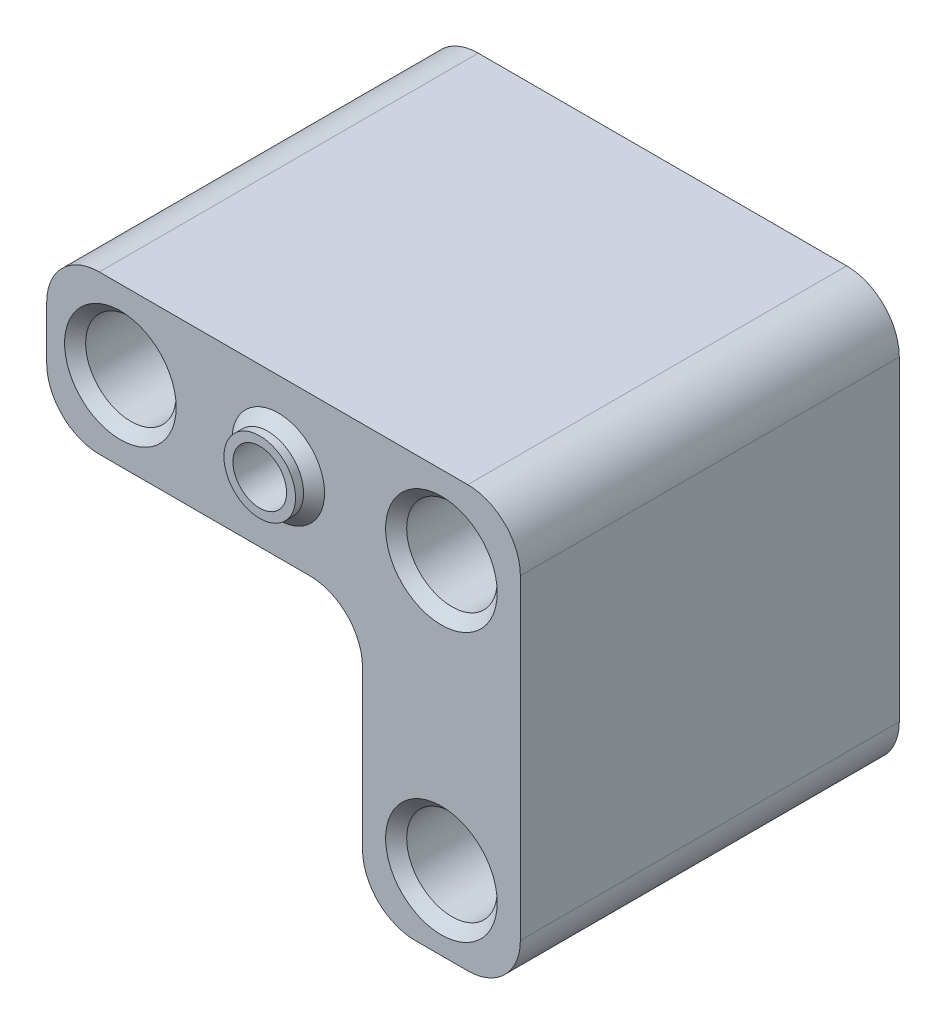
SolidWorks part; units mm, degrees
ref_plane "Front Plane" through (0, 0, 0) normal (0, 0, 1) x (1, 0, 0)
ref_plane "Top Plane" through (0, 0, 0) normal (0, 1, 0) x (1, 0, 0)
ref_plane "Right Plane" through (0, 0, 0) normal (1, 0, 0) x (0, 0, -1)
sketch "Sketch2" plane through (0, 0, 0) normal (0, 0, 1) x (1, 0, 0)
  line L1 (-311.5, 320) -> (-326.5, 320)
  line L2 (-311.5, 320) -> (-311.5, 360)
  line L3 (-311.5, 360) -> (-326.5, 360)
  line L4 (-326.5, 320) -> (-326.5, 360)
  line L5 (-311.5, 360) -> (-281.5, 360)
  line L6 (-311.5, 360) -> (-311.5, 345)
  line L7 (-311.5, 345) -> (-281.5, 345)
  line L8 (-281.5, 360) -> (-281.5, 345)
  line L10 (-281.5, 352.5) -> (-340.0828, 352.5) construction
  line L11 (-319, 320) -> (-319, 373.0529) construction
  line L12 (-303.5, 320) -> (-303.5, 373.0529) construction
  circle A0 centre (-319, 327) radius 2.55
  circle A1 centre (-288.5, 352.5) radius 2.55
  circle A2 centre (-319, 352.5) radius 2.55
  dimension "D7" = 5.1
  dimension "D8" = 5.1
  dimension "D11" = 0
  dimension "D13" = 5.1
  dimension "D1" = 15
  dimension "D2" = 15
  dimension "D4" = 30
  dimension "D5" = 40
  dimension "D9" = 7
  dimension "D10" = 7
  dimension "D12" = 0
extrude "Boss-Extrude1" add sketch "Sketch2" along normal blind 36 contours A1 | A2 | A0 | L2 L1 L4 L3 | L6 L7 L8 L5
sketch "Sketch3" plane through (0, 0, 36) normal (0, 0, 1) x (1, 0, 0)
  circle A0 centre (-319, 352.5) radius 4.3
  circle A1 centre (-319, 327) radius 4.3
  circle A2 centre (-288.5, 352.5) radius 4.3
  dimension "D1" = 8.6
extrude "Cut-Extrude1" cut sketch "Sketch3" against normal blind 30.6
sketch "Sketch4" plane through (0, 0, 0) normal (0, 0, -1) x (-1, 0, 0)
  line L0 (281.5, 352.5) -> (328.8705, 352.5)
  line L1 (281.5, 360) -> (281.5, 345) construction
  line L2 (311.5, 320) -> (311.5, 345) construction
  line L3 (307.55, 354.8383) -> (303.5, 357.1765)
  line L4 (303.5, 357.1765) -> (299.45, 354.8383)
  line L5 (299.45, 354.8383) -> (299.45, 350.1617)
  line L6 (299.45, 350.1617) -> (303.5, 347.8235)
  line L7 (303.5, 347.8235) -> (307.55, 350.1617)
  line L8 (307.55, 350.1617) -> (307.55, 354.8383)
  circle A0 centre (303.5, 352.5) radius 4.05
  circle A1 centre (288.5, 352.5) radius 2.55 construction
  circle A2 centre (303.5, 352.5) radius 4.05 construction
  dimension "D1" = 8.1
  dimension "D3" = 0
  dimension "D2" = 15
extrude "Cut-Extrude2" cut sketch "Sketch4" against normal blind 31.6 contours A0 | L5 L6 L7 L8 L3 L4
fillet "Fillet1" radius 5 6 edges at (-281.5, 360, 18) (-281.5, 345, 18) (-311.5, 345, 18) (-311.5, 320, 18) (-326.5, 320, 18) (-326.5, 360, 18)
chamfer "Chamfer1" distance 1 angle 45 3 edges at (-284.2, 352.5, 36) (-314.7, 352.5, 36) (-314.7, 327, 36)
sketch "Sketch8" plane through (0, 0, 31.6) normal (0, 0, -1) x (-1, 0, 0)
  line L0 (307.55, 350.1617) -> (299.45, 354.8383) construction
  line L2 (307.55, 354.8383) -> (299.45, 350.1617) construction
  circle A0 centre (303.5, 352.5) radius 2.55
  dimension "D1" = 5.1
extrude "Cut-Extrude3" cut sketch "Sketch8" against normal blind 10 contours A0
sketch "Sketch9" plane through (0, 0, 36) normal (0, 0, 1) x (1, 0, 0)
  circle A0 centre (-303.5, 352.5) radius 3.4
  circle A1 centre (-303.5, 352.5) radius 2.55
  dimension "D1" = 6.8
  dimension "D2" = 5.1
extrude "Boss-Extrude3" add sketch "Sketch9" along normal blind 1.76
chamfer "Chamfer3" distance 1 angle 45 1 edges at (-306.9, 352.5, 36)
mirror "Mirror2" about plane through (-326.5, 320, 36) normal (-1, 0, 0) of bodies 107
delete or keep bodies "Body-Delete/Keep 1" type delete bodies bodies 107
chamfer "Chamfer4" distance 1 angle 45 6 edges at (-351.525, 348.9926, 0) (-353.55, 352.5, 0) (-351.525, 356.0074, 0) (-347.475, 356.0074, 0) (-345.45, 352.5, 0) (-347.475, 348.9926, 0)
